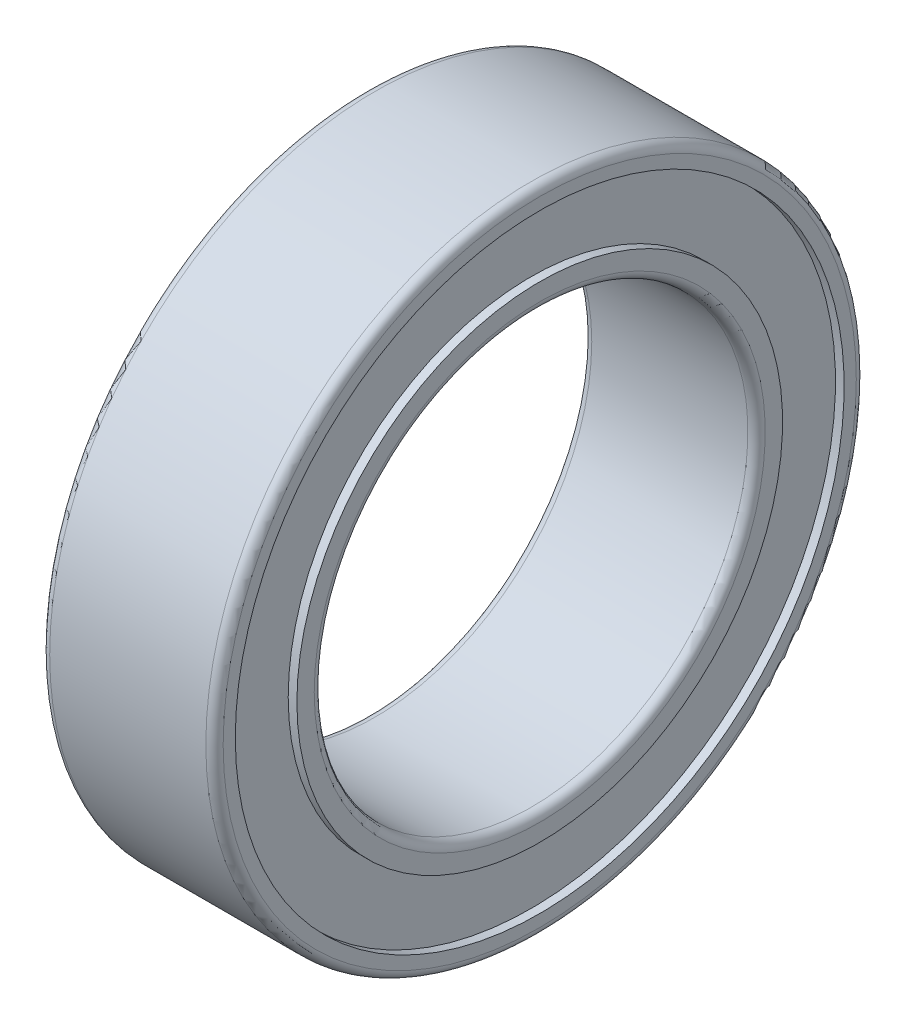
SolidWorks part; units mm, degrees
material "SUJ2"
ref_plane "Front Plane" through (0, 0, 0) normal (0, 0, 1) x (1, 0, 0)
ref_plane "Top Plane" through (0, 0, 0) normal (0, 1, 0) x (1, 0, 0)
ref_plane "Right Plane" through (0, 0, 0) normal (1, 0, 0) x (0, 0, -1)
sketch "Sketch1" plane through (0, 0, 0) normal (0, 0, 1) x (1, 0, 0)
  line L0 (0, 0) -> (4, 0) construction
  line L1 (0, 5) -> (4, 5)
  line L2 (0, 7.5) -> (4, 7.5)
  line L3 (0, 7.5) -> (0, 7.02)
  line L4 (0, 7.02) -> (0.2, 7.02)
  line L5 (4, 7.5) -> (4, 7.02)
  line L6 (0.2, 7.02) -> (0.2, 5.6)
  line L7 (0.2, 5.6) -> (0, 5.6)
  line L8 (0, 5.6) -> (0, 5)
  line L9 (4, 7.02) -> (3.8, 7.02)
  line L10 (3.8, 7.02) -> (3.8, 5.6)
  line L11 (3.8, 5.6) -> (4, 5.6)
  line L12 (4, 5.6) -> (4, 5)
  dimension "D" = 15
  dimension "B" = 4
  dimension "D_s" = 10
  dimension "MSM_1" = 14.04
  dimension "MSM_2" = 11.2
  dimension "MSM_3" = 0.2
revolve "Revolve1" add sketch "Sketch1" angle 360 about L0
fillet "Fillet1" radius 0.2 2 edges at (4, 0, 7.5) (0, 0, 7.5)
fillet "Fillet2" radius 0.2 2 edges at (4, 0, 5) (0, 0, 5)
